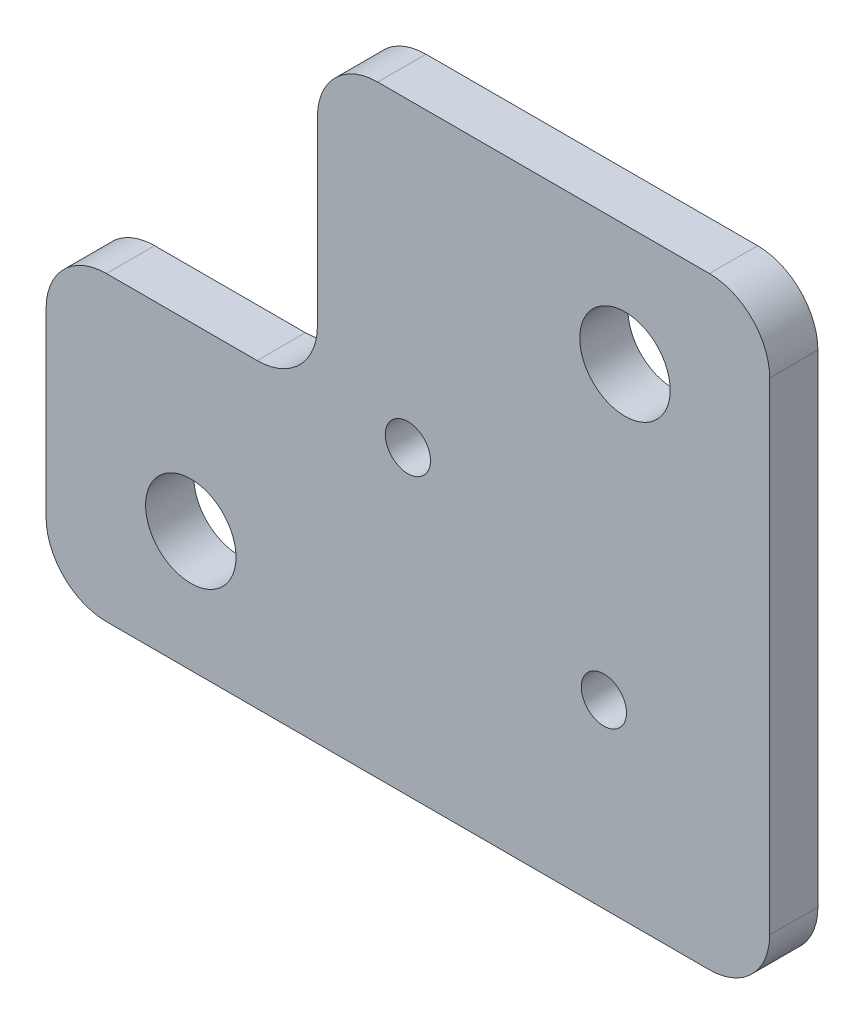
SolidWorks part; units mm, degrees
material "Латунь"
ref_plane "Спереди" through (0, 0, 0) normal (0, 0, 1) x (1, 0, 0)
ref_plane "Сверху" through (0, 0, 0) normal (0, 1, 0) x (1, 0, 0)
ref_plane "Справа" through (0, 0, 0) normal (1, 0, 0) x (0, 0, -1)
sketch "Эскиз1" plane through (0, 0, 0) normal (0, 0, 1) x (1, 0, 0)
  line L1 (-6, -5) -> (6, -5)
  line L2 (-6, -5) -> (-6, 5)
  line L3 (-6, 5) -> (6, 5)
  line L4 (6, -5) -> (6, 5)
  line L5 (-6, -5) -> (6, 5) construction
  line L6 (-6, 5) -> (6, -5) construction
  point P0 (0, 0)
  dimension "D1" = 12
  dimension "D2" = 10
extrude "Бобышка-Вытянуть1" add sketch "Эскиз1" along normal blind 0.8
sketch "Эскиз2" plane through (0, 0, 0.8) normal (0, 0, 1) x (1, 0, 0)
  line L0 (-6, -5) -> (6, 5) construction
  line L1 (-6, -5) -> (6, -5) construction
  line L3 (-6, 5) -> (-1.5, 5)
  line L4 (6, 5) -> (-6, 5) construction
  line L5 (6, -5) -> (6, 5) construction
  line L6 (-6, 5) -> (-6, 0)
  line L7 (-6, 0) -> (-1.5, 0)
  line L8 (-1.5, 5) -> (-1.5, 0)
  circle A0 centre (0, 0) radius 0.375
  circle A1 centre (-3.6, -3) radius 0.75
  circle A2 centre (3.6, 3) radius 0.75
  circle A3 centre (3.25, -2) radius 0.375
  dimension "D1" = 0.75
  dimension "D3" = 1.5
  dimension "D5" = 1.5
  dimension "D8" = 0.75
  dimension "D2" = 2
  dimension "D4" = 2
  dimension "D6" = 2.75
  dimension "D7" = 3
  dimension "D9" = 7.5
  dimension "D10" = 5
extrude "Вырез-Вытянуть1" cut sketch "Эскиз2" against normal up to next
fillet "Скругление1" radius 1 6 edges at (6, -5, 0.4) (-6, -5, 0.4) (6, 5, 0.4) (-1.5, 5, 0.4) (-1.5, 0, 0.4) (-6, 0, 0.4)
